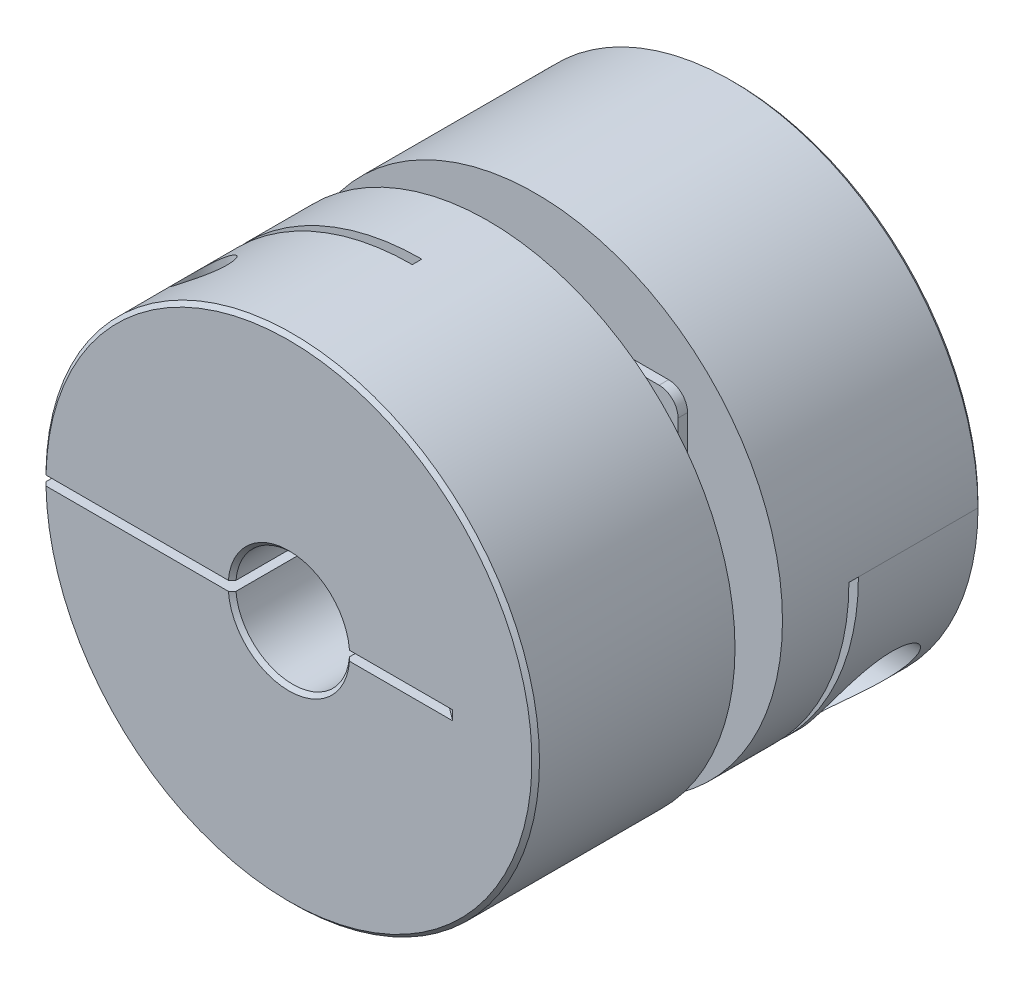
SolidWorks part; units mm, degrees
ref_plane "前视基准面" through (0, 0, 0) normal (0, 0, 1) x (1, 0, 0)
ref_plane "上视基准面" through (0, 0, 0) normal (0, 1, 0) x (1, 0, 0)
ref_plane "右视基准面" through (0, 0, 0) normal (1, 0, 0) x (0, 0, -1)
sketch "草图1" plane through (0, 0, 0) normal (0, 0, 1) x (1, 0, 0)
  line L1 (-8, -9) -> (8, -9)
  line L2 (-9, -8) -> (-9, 8)
  line L3 (-8, 9) -> (8, 9)
  line L4 (9, -8) -> (9, 8)
  line L5 (-9, -9) -> (9, 9) construction
  line L6 (-9, 9) -> (9, -9) construction
  arc A0 (-9, -8) -> (-8, -9) centre (-8, -8) ccw
  arc A1 (8, -9) -> (9, -8) centre (8, -8) ccw
  arc A2 (9, 8) -> (8, 9) centre (8, 8) ccw
  arc A3 (-8, 9) -> (-9, 8) centre (-8, 8) ccw
  point P0 (0, 0)
  dimension "D3" = 1
  dimension "D1" = 18
  dimension "D2" = 18
extrude "凸台-拉伸1" add sketch "草图1" along normal mid plane 0.5
sketch "草图2" plane through (0, 0, 0.25) normal (0, 0, 1) x (1, 0, 0)
  line L0 (0, 9) -> (0, 0) construction
  line L1 (0, 0) -> (-6.364, 6.364) construction
  line L2 (0, 0) -> (-6.6481, 0) construction
  circle A0 centre (0, 0) radius 9 construction
  circle A1 centre (-6.364, 6.364) radius 1.5
  circle A2 centre (6.364, 6.364) radius 1.5
  circle A3 centre (6.364, -6.364) radius 1.5
  circle A4 centre (-6.364, -6.364) radius 1.5
  dimension "D2" = 18
  dimension "D3" = 3
  dimension "D1" = 45
extrude "凸台-拉伸2" add sketch "草图2" along normal blind 1
sketch "草图4" plane through (0, 0, 1.25) normal (0, 0, 1) x (1, 0, 0)
  circle A0 centre (0, 0) radius 13
  dimension "D1" = 26
extrude "凸台-拉伸3" add sketch "草图4" along normal blind 10.5
mirror "镜向1" about plane through (0, 0, 0) normal (0, 0, 1) of "凸台-拉伸2", "凸台-拉伸3"
sketch "草图6" plane through (0, 0, -11.75) normal (0, 0, -1) x (-1, 0, 0)
  circle A0 centre (0, 0) radius 4
  dimension "D1" = 8
extrude "切除-拉伸1" cut sketch "草图6" against normal blind 11.5
sketch "草图7" plane through (0, 0, 11.75) normal (0, 0, 1) x (1, 0, 0)
  circle A0 centre (0, 0) radius 3
  dimension "D1" = 6
extrude "切除-拉伸2" cut sketch "草图7" against normal blind 13
sketch "草图9" plane through (0, 0, 0) normal (0, 1, 0) x (1, 0, 0)
  line L0 (-13, 11.75) -> (-13, 1.25) construction
  line L1 (-13, 4.75) -> (13, 4.75)
  line L2 (-13, 4.75) -> (-13, 5.25)
  line L3 (-13, 5.25) -> (13, 5.25)
  line L4 (13, 4.75) -> (13, 5.25)
  line L5 (13, 1.25) -> (13, 11.75) construction
  line L6 (13, 11.75) -> (-13, 11.75) construction
  dimension "D1" = 7
  dimension "D2" = 0.5
extrude "切除-拉伸3" cut sketch "草图9" against normal through all
sketch "草图10" plane through (0, 0, 0) normal (1, 0, 0) x (0, 0, -1)
  line L0 (-11.75, -13) -> (-1.25, -13) construction
  line L1 (-4.75, -13) -> (-5.25, -13)
  line L2 (-4.75, -13) -> (-4.75, 13)
  line L3 (-4.75, 13) -> (-5.25, 13)
  line L4 (-5.25, -13) -> (-5.25, 13)
  line L5 (-1.25, 13) -> (-11.75, 13) construction
  line L6 (-11.75, 13) -> (-11.75, -13) construction
  dimension "D1" = 7
  dimension "D2" = 0.5
extrude "切除-拉伸4" cut sketch "草图10" against normal through all
sketch "草图11" plane through (0, 0, 0) normal (0, 1, 0) x (1, 0, 0)
  line L0 (0, -5.25) -> (8.6258, -11.75)
  line L1 (0, -5.25) -> (-13, -5.25) construction
  line L2 (-13, -5.25) -> (-13, -11.75) construction
  line L3 (-3, -11.75) -> (3, -11.75) construction
  line L4 (0, -5.25) -> (-13, -5.25)
  line L5 (-13, -5.25) -> (-13, -11.75)
  line L6 (-13, -11.75) -> (8.6258, -11.75)
  dimension "D1" = 143
extrude "切除-拉伸5" cut sketch "草图11" against normal mid plane 0.5
sketch "草图12" plane through (0, 0, 0) normal (1, 0, 0) x (0, 0, -1)
  line L0 (5.25, 0) -> (5.25, -13)
  line L1 (5.25, -13) -> (11.75, -13)
  line L2 (11.75, -13) -> (11.75, 8.6258)
  line L3 (5.25, 0) -> (11.75, 8.6258)
  dimension "D1" = 143
extrude "切除-拉伸6" cut sketch "草图12" against normal mid plane 0.5
ref_plane "基准面1" through (13, 0, 0) normal (1, 0, 0) x (0, 0, -1)
hole_wizard "打孔尺寸根据内六角圆柱头螺钉的类型2" positions "草图14" profile "草图15" counterbore size "M3" standard "Gb"
sketch "草图14" plane through (13, 0, 0) normal (1, 0, 0) x (0, 0, -1)
  line L0 (11.75, -12.9976) -> (11.75, 13) construction
  line L1 (0, 0) -> (12.1298, 0) construction
  point P0 (8.25, -8)
  dimension "D1" = 3.5
  dimension "D2" = 8
sketch "草图15" plane through (13, -8, -8.25) normal (0, 1, 0) x (0, 0, -1)
  line L0 (0, 0) -> (0, 13.9614)
  line L1 (0, 13.9614) -> (1.6, 13)
  line L2 (1.6, 13) -> (1.6, 9)
  line L3 (1.6, 9) -> (2.5, 9)
  line L4 (2.5, 9) -> (2.5, 0)
  line L5 (2.5, 0) -> (0, 0)
  line L10 (0, 13.9614) -> (-1.6, 13) construction
  line L11 (0, -6.35) -> (0, 107.95) construction
  dimension "孔直径" = 3.2
  dimension "孔深度" = 13
  dimension "柱形沉头孔直径" = 5
  dimension "柱形沉头孔深度" = 9
  dimension "导头角度" = 118
hole_wizard "M3 螺纹孔2" positions "草图17" profile "草图18" tap size "M3" standard "Iso" end condition through all
sketch "草图17" plane through (-0.25, 0, 0) normal (1, 0, 0) x (0, 0, -1)
  point P0 (8.25, -8)
sketch "草图18" plane through (-0.25, -8, -8.25) normal (0, 1, 0) x (0, 0, -1)
  line L0 (0, 0) -> (0, 12.75)
  line L1 (0, 12.75) -> (1.25, 12.75)
  line L2 (1.25, 12.75) -> (1.25, 0)
  line L5 (1.25, 0) -> (0, 0)
  line L11 (0, -6.35) -> (0, 107.95) construction
  dimension "通孔螺纹孔钻头直径" = 2.5
  dimension "通孔螺纹孔钻头深度" = 12.75
cosmetic thread "孔螺蚊线1" parameters "D2"=3
ref_plane "基准面2" through (0, -13, 0) normal (0, 1, 0) x (1, 0, 0)
hole_wizard "打孔尺寸根据内六角圆柱头螺钉的类型2" positions "草图21" profile "草图19" counterbore size "M2.5" standard "Gb"
sketch "草图21" plane through (0, -13, 0) normal (0, 1, 0) x (1, 0, 0)
  line L0 (-12.9976, -11.75) -> (13, -11.75) construction
  line L1 (0, 0) -> (0, -11.9006) construction
  point P0 (-8, -8.25)
  dimension "D1" = 3.5
  dimension "D2" = 8
sketch "草图19" plane through (-8, -13, 8.25) normal (1, 0, 0) x (0, 0, -1)
  line L0 (0, 0) -> (0, 13.9914)
  line L1 (0, 13.9914) -> (1.65, 13)
  line L2 (1.65, 13) -> (1.65, 9)
  line L3 (1.65, 9) -> (2.5, 9)
  line L4 (2.5, 9) -> (2.5, 0)
  line L5 (2.5, 0) -> (0, 0)
  line L10 (0, 13.9914) -> (-1.65, 13) construction
  line L11 (0, -6.35) -> (0, 107.95) construction
  dimension "孔直径" = 3.3
  dimension "孔深度" = 13
  dimension "柱形沉头孔直径" = 5
  dimension "柱形沉头孔深度" = 9
  dimension "导头角度" = 118
hole_wizard "M3 螺纹孔1" positions "草图23" profile "草图24" tap size "M3" standard "Iso" end condition through all
sketch "草图23" plane through (0, 0.25, 0) normal (0, -1, 0) x (-1, 0, 0)
  point P0 (8, -8.25)
sketch "草图24" plane through (-8, 0.25, 8.25) normal (1, 0, 0) x (0, 0, -1)
  line L0 (0, 0) -> (0, 12.75)
  line L1 (0, 12.75) -> (1.25, 12.75)
  line L2 (1.25, 12.75) -> (1.25, 0)
  line L5 (1.25, 0) -> (0, 0)
  line L11 (0, -6.35) -> (0, 107.95) construction
  dimension "通孔螺纹孔钻头直径" = 2.5
  dimension "通孔螺纹孔钻头深度" = 12.75
cosmetic thread "孔螺蚊线2" parameters "D2"=3
chamfer "倒角1" distance 0.2 angle 45 6 edges at (13, 0, 11.75) (0, -3, 11.75) (0, 3, 11.75) (4, 0, -11.75) (-4, 0, -11.75) (0, 13, -11.75)
